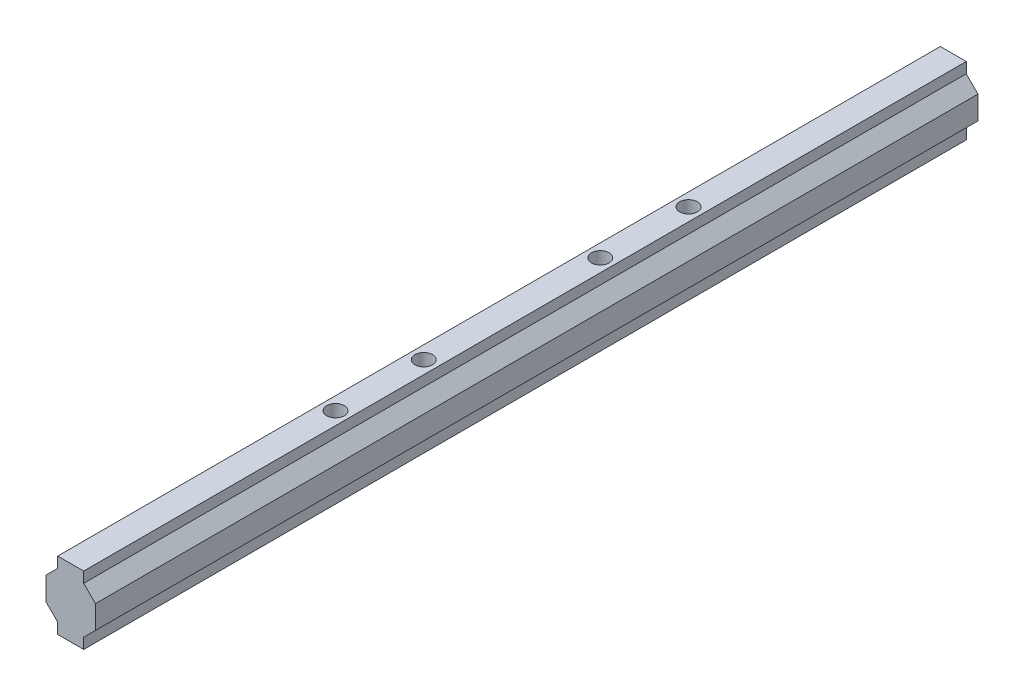
SolidWorks part; units mm, degrees
ref_plane "Front Plane" through (0, 0, 0) normal (0, 0, 1) x (1, 0, 0)
ref_plane "Top Plane" through (0, 0, 0) normal (0, 1, 0) x (1, 0, 0)
ref_plane "Right Plane" through (0, 0, 0) normal (1, 0, 0) x (0, 0, -1)
sketch "Sketch1" plane through (0, 0, 116.1066) normal (0, 0, 1) x (1, 0, 0)
  line L0 (-39.5503, 5.2942) -> (-36.8896, 7.9549)
  line L1 (-36.8896, 7.9549) -> (-36.8896, 10.362)
  line L2 (-36.8896, 10.362) -> (-31.011, 10.362)
  line L3 (-31.011, 7.9549) -> (-28.3503, 5.2942)
  line L4 (-28.3503, 5.2942) -> (-28.3503, 0.0298)
  line L5 (-28.3503, 0.0298) -> (-31.011, -2.6309)
  line L6 (-31.011, -2.6309) -> (-31.011, -5.038)
  line L7 (-31.011, -5.038) -> (-36.8896, -5.038)
  line L8 (-36.8896, -5.038) -> (-36.8896, -2.6309)
  line L9 (-36.8896, -2.6309) -> (-39.5503, 0.0298)
  line L10 (-39.5503, 0.0298) -> (-39.5503, 5.2942)
  line L11 (-31.011, 10.362) -> (-31.011, 7.9549)
  line L12 (-37.3896, 10.862) -> (-30.511, 10.862) construction
  line L13 (-37.3896, -5.538) -> (-30.511, -5.538) construction
  line L14 (-27.8503, 5.4185) -> (-27.8503, -0.0945) construction
  line L15 (-40.0503, 5.4185) -> (-40.0503, -0.0945) construction
  line L16 (-39.9917, 5.5599) -> (-37.3896, 8.162) construction
  line L17 (-37.3896, 8.162) -> (-37.3896, 10.862) construction
  line L18 (-30.511, 8.162) -> (-30.511, 10.862) construction
  line L19 (-27.9089, 5.5599) -> (-30.511, 8.162) construction
  line L20 (-27.9089, -0.2359) -> (-30.511, -2.838) construction
  line L21 (-30.511, -2.838) -> (-30.511, -5.538) construction
  line L22 (-37.3896, -2.838) -> (-37.3896, -5.538) construction
  line L23 (-39.9917, -0.2359) -> (-37.3896, -2.838) construction
  point P24 (-37.3896, 9.512)
  dimension "D1" = 0.5
  dimension "D2" = 0.5
  dimension "D3" = 0.5
  dimension "D4" = 0.5
  dimension "D5" = 0.5
  dimension "D6" = 0.5
  dimension "D7" = 0.5
  dimension "D8" = 0.5
  dimension "D9" = 0.5
  dimension "D10" = 0.5
  dimension "D11" = 0.5
  dimension "D12" = 0.5
extrude "Boss-Extrude1" add sketch "Sketch1" along normal blind 200
sketch "Sketch4" plane through (0, -5.038, 0) normal (0, -1, 0) x (-1, 0, 0)
  line L0 (33.9503, -116.1066) -> (33.9503, -223.2877) construction
  line L1 (36.8896, -116.1066) -> (31.011, -116.1066) construction
  line L2 (36.8896, -216.1066) -> (-7.4832, -216.1066) construction
  line L3 (36.8896, -316.1066) -> (36.8896, -116.1066) construction
  circle A0 centre (33.9503, -176.1066) radius 2
  circle A3 centre (33.9503, -196.1066) radius 2
  circle A4 centre (33.9503, -236.1066) radius 2
  circle A5 centre (33.9503, -256.1066) radius 2
  dimension "D1" = 0
  dimension "D2" = 0
  dimension "D3" = 20
  dimension "D4" = 20
  dimension "D5" = 4
  dimension "D6" = 4
extrude "Cut-Extrude1" cut sketch "Sketch4" against normal blind 40
